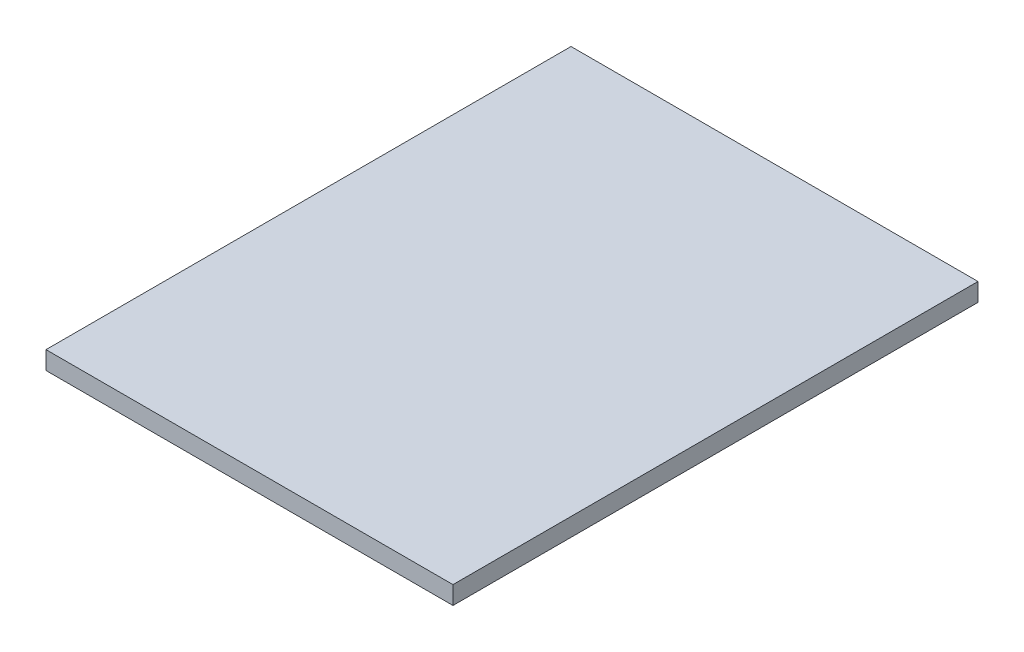
SolidWorks part; units mm, degrees
ref_plane "Plan de face" through (0, 0, 0) normal (0, 0, 1) x (1, 0, 0)
ref_plane "Plan de dessus" through (0, 0, 0) normal (0, 1, 0) x (1, 0, 0)
ref_plane "Plan de droite" through (0, 0, 0) normal (1, 0, 0) x (0, 0, -1)
sketch "Esquisse1" plane through (0, 0, 0) normal (0, 1, 0) x (1, 0, 0)
  line L1 (0, 0) -> (22.48, 0)
  line L2 (0, 0) -> (0, 29)
  line L3 (0, 29) -> (22.48, 29)
  line L4 (22.48, 0) -> (22.48, 29)
  dimension "D1" = 22.48
  dimension "D2" = 29
extrude "Boss.-Extru.2" add sketch "Esquisse1" along normal blind 1
